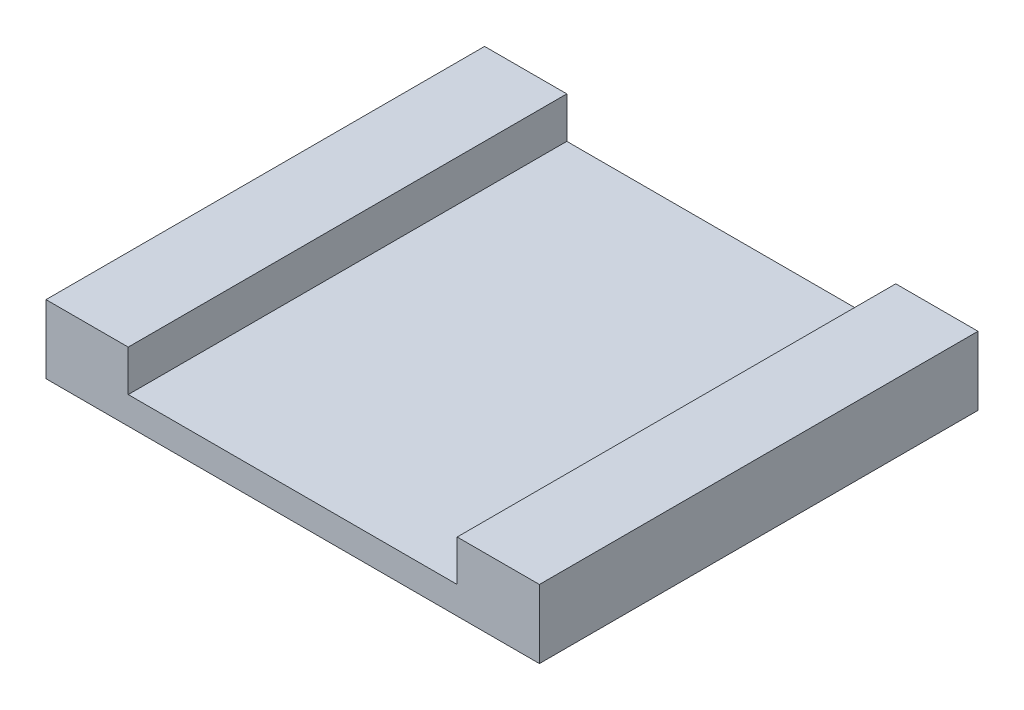
SolidWorks part; units mm, degrees
ref_plane "Front Plane" through (0, 0, 0) normal (0, 0, 1) x (1, 0, 0)
ref_plane "Top Plane" through (0, 0, 0) normal (0, 1, 0) x (1, 0, 0)
ref_plane "Right Plane" through (0, 0, 0) normal (1, 0, 0) x (0, 0, -1)
sketch "Sketch1" plane through (0, 0, 0) normal (0, 0, 1) x (1, 0, 0)
  line L0 (0, 0) -> (76.2, 0)
  line L1 (76.2, 0) -> (76.2, 19.05)
  line L2 (76.2, 19.05) -> (114.3, 19.05)
  line L3 (114.3, 19.05) -> (114.3, -12.7)
  line L4 (114.3, -12.7) -> (0, -12.7)
  line L5 (0, -12.7) -> (0, 0)
  dimension "D1" = 12.7
  dimension "D2" = 19.05
  dimension "D3" = 38.1
  dimension "D4" = 76.2
extrude "Boss-Extrude1" add sketch "Sketch1" against normal blind 203.2
mirror "Mirror1" about plane through (0, -12.7, -203.2) normal (-1, 0, 0) of "Boss-Extrude1"
